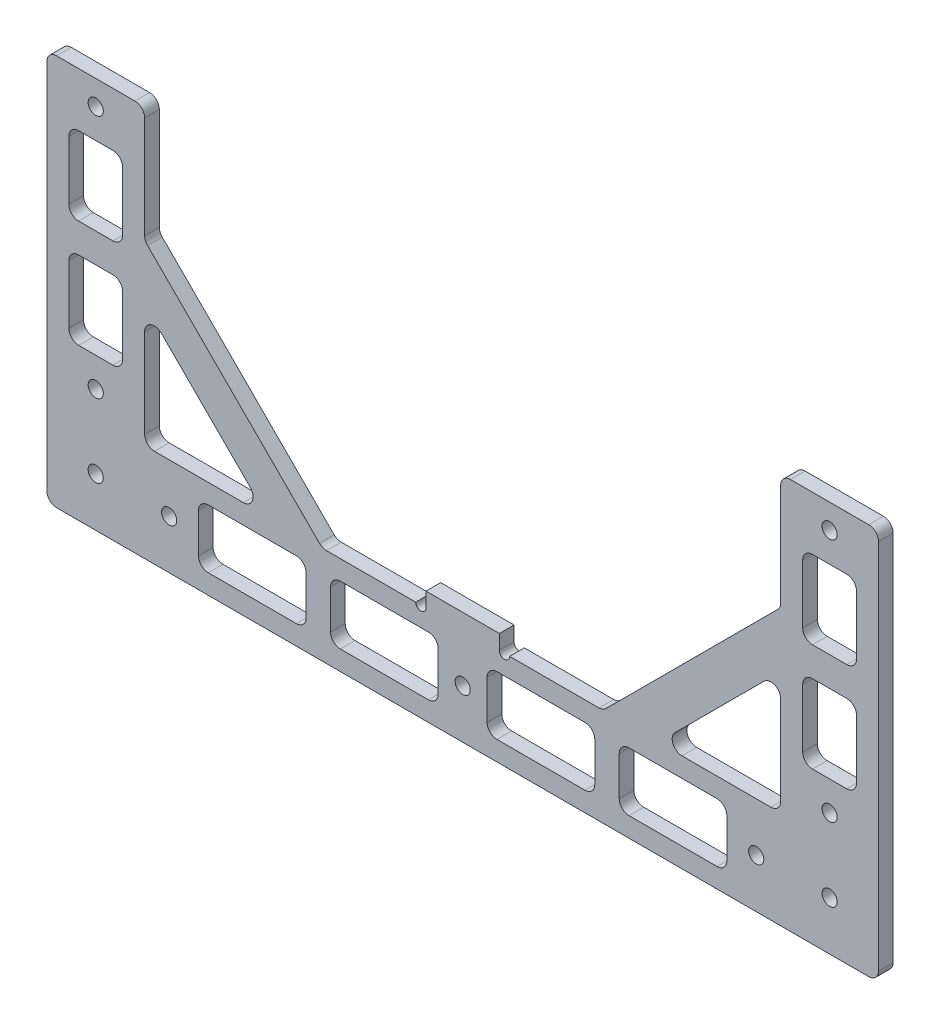
SolidWorks part; units mm, degrees
material "环氧树脂板"
ref_plane "前视基准面" through (0, 0, 0) normal (0, 0, 1) x (1, 0, 0)
ref_plane "上视基准面" through (0, 0, 0) normal (0, 1, 0) x (1, 0, 0)
ref_plane "右视基准面" through (0, 0, 0) normal (1, 0, 0) x (0, 0, -1)
sketch "草图1" plane through (0, 0, 0) normal (0, 0, 1) x (1, 0, 0)
  line L0 (0, 0) -> (0, 80)
  line L1 (0, 80) -> (20, 80)
  line L2 (20, 80) -> (20, 56.3137)
  line L3 (20, 20) -> (45, 20)
  line L4 (150, 20) -> (150, 45)
  line L5 (150, 80) -> (170, 80)
  line L6 (170, 80) -> (170, 0)
  line L7 (170, 0) -> (0, 0)
  line L8 (10, 10) -> (106.0066, 10) construction
  line L9 (10, 80) -> (10, 75) construction
  line L10 (85, 0) -> (85, 45.5189) construction
  line L11 (20, 56.3137) -> (56.3137, 20)
  line L12 (20, 45) -> (45, 20)
  line L13 (150, 45) -> (125, 20)
  line L14 (150, 56.3137) -> (113.6863, 20)
  line L15 (20, 45) -> (20, 20)
  line L16 (56.3137, 20) -> (77.5, 20)
  line L17 (125, 20) -> (150, 20)
  line L18 (150, 56.3137) -> (150, 80)
  line L19 (77.5, 20) -> (77.5, 23)
  line L20 (77.5, 23) -> (92.5, 23)
  line L21 (92.5, 23) -> (92.5, 20)
  line L22 (92.5, 20) -> (113.6863, 20)
  line L23 (154.5, 47) -> (165.5, 47)
  line L24 (15.5, 31) -> (4.5, 31)
  line L25 (15.5, 31) -> (15.5, 47)
  line L26 (15.5, 47) -> (4.5, 47)
  line L27 (4.5, 31) -> (4.5, 47)
  line L28 (15.5, 31) -> (4.5, 47) construction
  line L29 (15.5, 47) -> (4.5, 31) construction
  line L30 (15.5, 53) -> (4.5, 53)
  line L31 (15.5, 53) -> (15.5, 69)
  line L32 (15.5, 69) -> (4.5, 69)
  line L33 (4.5, 53) -> (4.5, 69)
  line L34 (15.5, 53) -> (4.5, 69) construction
  line L35 (15.5, 69) -> (4.5, 53) construction
  line L36 (165.5, 31) -> (165.5, 47)
  line L37 (154.5, 31) -> (165.5, 31)
  line L38 (154.5, 31) -> (154.5, 47)
  line L39 (154.5, 69) -> (165.5, 69)
  line L40 (165.5, 53) -> (165.5, 69)
  line L41 (154.5, 53) -> (165.5, 53)
  line L42 (154.5, 53) -> (154.5, 69)
  line L43 (117, 16) -> (139, 16)
  line L44 (53, 4) -> (31, 4)
  line L45 (53, 4) -> (53, 16)
  line L46 (53, 16) -> (31, 16)
  line L47 (31, 4) -> (31, 16)
  line L48 (53, 4) -> (31, 16) construction
  line L49 (53, 16) -> (31, 4) construction
  line L50 (80, 4) -> (58, 4)
  line L51 (80, 4) -> (80, 16)
  line L52 (80, 16) -> (58, 16)
  line L53 (58, 4) -> (58, 16)
  line L54 (80, 4) -> (58, 16) construction
  line L55 (80, 16) -> (58, 4) construction
  line L56 (139, 4) -> (139, 16)
  line L57 (117, 4) -> (139, 4)
  line L58 (117, 4) -> (117, 16)
  line L59 (90, 16) -> (112, 16)
  line L60 (112, 4) -> (112, 16)
  line L61 (90, 4) -> (112, 4)
  line L62 (90, 4) -> (90, 16)
  circle A0 centre (10, 10) radius 1.55
  circle A1 centre (10, 75) radius 1.55
  circle A2 centre (25, 10) radius 1.55
  circle A3 centre (85, 10) radius 1.55
  circle A5 centre (160, 10) radius 1.55
  circle A6 centre (160, 75) radius 1.55
  circle A7 centre (93.55, 20) radius 1.05
  circle A8 centre (76.45, 20) radius 1.05
  circle A9 centre (145, 10) radius 1.55
  circle A10 centre (10, 25) radius 1.55
  circle A11 centre (160, 25) radius 1.55
  point P48 (10, 39)
  point P53 (10, 61)
  point P65 (42, 10)
  point P70 (69, 10)
  dimension "D8" = 3.1
  dimension "D14" = 2.1
  dimension "D1" = 20
  dimension "D2" = 20
  dimension "D3" = 20
  dimension "D4" = 150
  dimension "D5" = 80
  dimension "D6" = 5
  dimension "D7" = 5
  dimension "D9" = 45
  dimension "D10" = 8
  dimension "D11" = 25
  dimension "D12" = 3
  dimension "D13" = 15
  dimension "D15" = 5
  dimension "D16" = 4.5
  dimension "D17" = 4.5
  dimension "D18" = 6
  dimension "D19" = 6
  dimension "D20" = 6
  dimension "D21" = 6
  dimension "D22" = 5
  dimension "D23" = 5
  dimension "D24" = 4
extrude "凸台-拉伸1" add sketch "草图1" along normal blind 3 contours A8 L16 L11 L2 L1 L0 L7 L6 L5 L18 L14 L22 A7 L21 L20 L19 L15 L12 L3 L17 L13 L4 A0 A1 A2 A3 A5 A6
fillet "圆角1" radius 2 48 edges at (113.6863, 20, 1.5) (150, 56.3137, 1.5) (150, 80, 1.5) (170, 80, 1.5) (170, 0, 1.5) (0, 0, 1.5) (20, 80, 1.5) (20, 56.3137, 1.5) (56.3137, 20, 1.5) (0, 80, 1.5) (150, 20, 1.5) (125, 20, 1.5) (15.5, 31, 1.5) (15.5, 47, 1.5) (4.5, 47, 1.5) (4.5, 31, 1.5) (15.5, 53, 1.5) (15.5, 69, 1.5) (4.5, 69, 1.5) (4.5, 53, 1.5) (165.5, 31, 1.5) (165.5, 47, 1.5) (154.5, 47, 1.5) (154.5, 31, 1.5) (165.5, 53, 1.5) (165.5, 69, 1.5) (154.5, 69, 1.5) (154.5, 53, 1.5) (53, 4, 1.5) (53, 16, 1.5) (31, 16, 1.5) (31, 4, 1.5) (80, 4, 1.5) (80, 16, 1.5) (58, 16, 1.5) (58, 4, 1.5) (139, 4, 1.5) (139, 16, 1.5) (117, 16, 1.5) (117, 4, 1.5) (112, 4, 1.5) (112, 16, 1.5) (90, 16, 1.5) (90, 4, 1.5) (150, 45, 1.5) (20, 20, 1.5) (45, 20, 1.5) (20, 45, 1.5)
